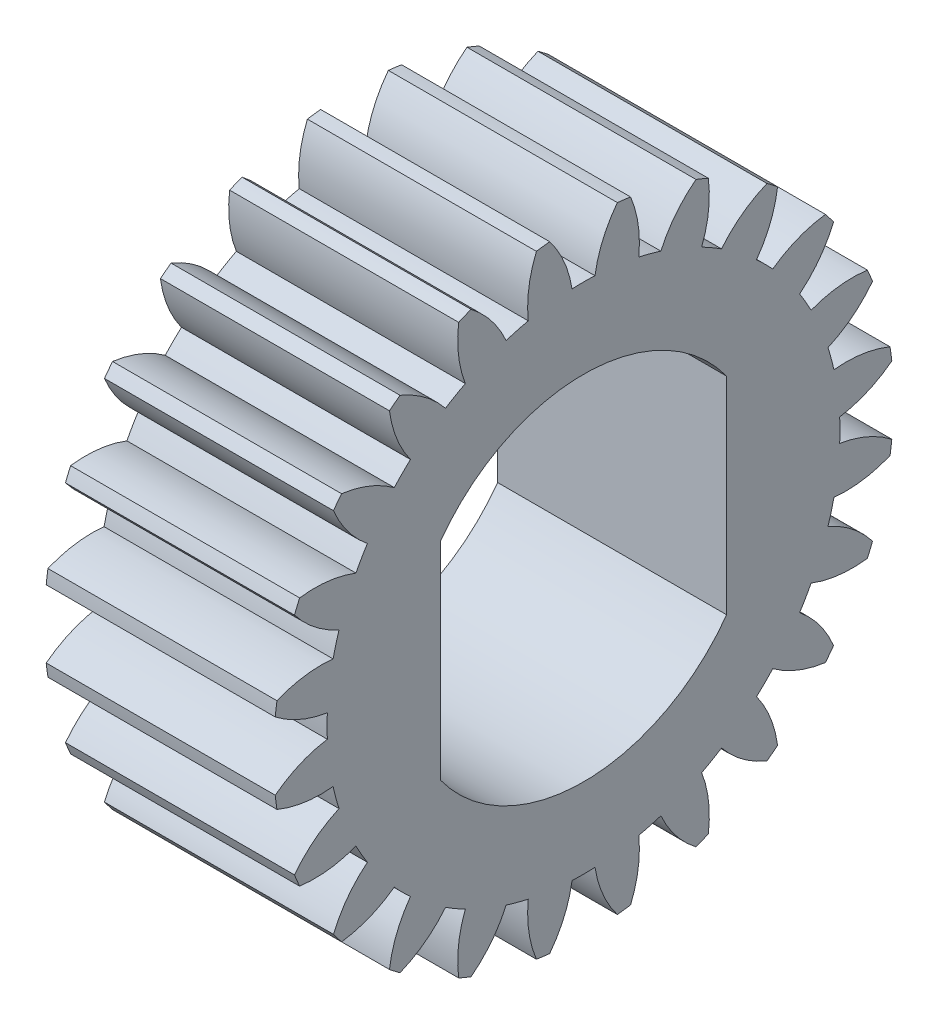
SolidWorks part; units mm, degrees
ref_plane "Plane1" through (0, 0, 0) normal (0, 0, 1) x (1, 0, 0)
ref_plane "Plane2" through (0, 0, 0) normal (0, 1, 0) x (1, 0, 0)
ref_plane "Plane3" through (0, 0, 0) normal (1, 0, 0) x (0, 0, -1)
other "Configuration Table"
sketch "HoldingSke" plane through (0, 0, 0) normal (0, 1, 0) x (1, 0, 0)
  line L0 (0, 0) -> (0.7308, -0.3254)
  line L1 (-15, 0) -> (100, 0) construction
  line L2 (0, 0) -> (-2.1039, 2.3779)
  line L3 (0, 0) -> (-11.863, 4.5341)
  line L4 (0, 0) -> (7.8894, 3.5126)
  line L5 (0, 0) -> (-46.8476, -17.4728)
  line L6 (0, 0) -> (-9.9476, -6.7116)
  line L7 (-2.1039, 2.3779) -> (8.6586, 51.2059)
  line L8 (-76.2, 54.61) -> (-72.9, 54.61)
  line L9 (-71.009, 38.7566) -> (-53.1078, 45.2721)
  line L10 (-76.2, 71.12) -> (104.1128, 71.12)
  line L11 (0, 0) -> (-12, 0)
  line L12 (-76.2, 101.6) -> (-76.155, 101.6)
  line L13 (24.9733, 27.94) -> (52.9518, 28.4284)
  line L14 (24.9733, 27.94) -> (24.9743, 27.94)
  line L15 (24.9733, 27.94) -> (100.4006, 29.5858)
  line L16 (-63.627, -1.25) -> (-12.827, -1.25)
  circle A0 centre (0, 0) radius 12
  circle A1 centre (0, 0) radius 13.4365
  circle A2 centre (0, 0) radius 37.5
  circle A3 centre (0, 0) radius 12
  dimension "MHD" = 26.873
  dimension "Hub_dia" = 75
  dimension "Bore" = 24
  dimension "MBD" = 24
  dimension "Num_teeth" = 24
  dimension "Pitch" = 0.8
  dimension "Overall_len" = 50
  dimension "Show_teeth" = 24
  dimension "Thickness" = 12
  dimension "OAL" = 50.0001
  dimension "T_dim" = 3.3
  dimension "Ap" = 20
  dimension "H" = 19.05
  dimension "Pitch_radius" = 180.3128
  dimension "Width" = 12
  dimension "Backlash" = 0.045
  dimension "Addendum_fac" = 1
  dimension "Dedendum_fac" = 1.25
  dimension "Clearance_fac" = 0.25
  dimension "Dedendum_add" = 0.001
  dimension "Module" = 1.25
sketch "BasProSke" plane through (0, 0, 0) normal (0, 1, 0) x (1, 0, 0)
  line L0 (-10, 0) -> (60, 0) construction
  line L1 (0, 0) -> (0, 16.25)
  line L2 (0, 0) -> (12, 0)
  line L3 (12, 0) -> (12, 16.25)
  line L4 (12, 16.25) -> (0, 16.25)
  dimension "Thickness" = 12
  dimension "Diameter" = 32.5
revolve "Base-Revolve" add sketch "BasProSke" angle 360 about L0
sketch "TooCutSke" plane through (0, 0, 0) normal (1, 0, 0) x (0, 0, -1)
  line L1 (0, 0) -> (0, 107) construction
  line L2 (0, 0) -> (-1.0598, 14.9625) construction
  line L3 (0, 0) -> (-3.9087, 29.6895) construction
  line L4 (-1.0598, 14.9625) -> (-1.9543, 14.8447) construction
  arc A0 (0.6004, 13.4231) -> (-0.6004, 13.4231) centre (0, 0) ccw
  arc A1 (1.7918, 16.1765) -> (-1.7918, 16.1765) centre (0, 0) ccw
  circle A2 centre (0, 0) radius 15 construction
  circle A3 centre (0, 0) radius 14.0954 construction
  arc A4 (-0.6004, 13.4231) -> (-1.7918, 16.1765) centre (-6.5279, 12.4927) ccw
  arc A5 (1.7918, 16.1765) -> (0.6004, 13.4231) centre (6.5279, 12.4927) ccw
  dimension "Root_dia" = 26.873
  dimension "Overcut_dia" = 32.5508
  dimension "Pitch_dia" = 30
  dimension "Base_dia" = 28.1908
  dimension "Flank_rad" = 6
  dimension "Half_ang" = 7.5
  dimension "Half_CT" = 0.9023
extrude "ToothCut" cut sketch "TooCutSke" along normal through all
fillet "Breaks" [suppressed] radius 0.025
fillet "RootFillets" [suppressed] radius 0.3135
pattern_circular "TeethCuts" count 24 every 15 about axis through (-10, 0, 0) along (1, 0, 0) of "ToothCut", "RootFillets", "Breaks"
sketch "HubNeaOneSke" plane through (0, 0, 0) normal (-1, 0, 0) x (0, 0, 1)
  circle A0 centre (0, 0) radius 13.4365
  dimension "Diameter" = 26.873
extrude "HubNearOne" [suppressed] add sketch "HubNeaOneSke" along normal blind 38.0001
sketch "HubNeaBotSke" plane through (0, 0, 0) normal (-1, 0, 0) x (0, 0, 1)
  circle A0 centre (0, 0) radius 13.4365
  dimension "Diameter" = 26.873
extrude "HubNearBoth" [suppressed] add sketch "HubNeaBotSke" along normal blind 19
ref_plane "FarPln" through (12, 0, 0) normal (1, 0, 0) x (0, 0, -1)
sketch "HubFarSke" plane through (12, 0, 0) normal (1, 0, 0) x (0, 0, -1)
  circle A0 centre (0, 0) radius 13.4365
  dimension "Diameter" = 26.873
extrude "HubFar" [suppressed] add sketch "HubFarSke" along normal blind 19
sketch "BorSke" plane through (0, 0, 0) normal (1, 0, 0) x (0, 0, -1)
  circle A0 centre (0, 0) radius 12
  dimension "Diameter" = 24
extrude "Bore" cut sketch "BorSke" along normal mid plane 100.0001
sketch "KeySke" plane through (0, 0, 0) normal (1, 0, 0) x (0, 0, -1)
  line L0 (-4, 0) -> (-4, 15.3)
  line L1 (-4, 15.3) -> (4, 15.3)
  line L2 (4, 15.3) -> (4, 0)
  line L3 (0, 0) -> (0, 34) construction
  line L4 (-4, 0) -> (4, 0)
  dimension "Offset" = 15.3
  dimension "Width" = 8
extrude "Keyway" [suppressed] cut sketch "KeySke" along normal mid plane 100.0001
pattern_circular "Keyway2" [suppressed] count 2 every 90 about axis through (-10, 0, 0) along (1, 0, 0)
sketch "草图1" plane through (0, 0, 0) normal (-1, 0, 0) x (0, 0, 1)
  circle A0 centre (0, 0) radius 9.25
  circle A1 centre (0, 0) radius 12
  dimension "D1" = 18.5
  dimension "D2" = 24
extrude "凸台-拉伸1" add sketch "草图1" against normal through all
sketch "草图2" plane through (0, 0, 0) normal (-1, 0, 0) x (0, 0, 1)
  line L0 (-7.5, 5.4141) -> (-7.5, -5.4141)
  line L8 (0, 9.25) -> (0, 0) construction
  line L9 (7.5, 5.4141) -> (7.5, -5.4141)
  circle A0 centre (0, 0) radius 9.25 construction
  arc A1 (-7.5, 5.4141) -> (-7.5, -5.4141) centre (0, 0) ccw
  arc A2 (7.5, 5.4141) -> (7.5, -5.4141) centre (0, 0) cw
  dimension "D1" = 7.5
extrude "凸台-拉伸2" add sketch "草图2" against normal through all
equation "' \"Module@HoldingSke\" = 6.35"
equation "' \"Num_teeth@HoldingSke\" = 12"
equation "' \"Ap@HoldingSke\" =  20"
equation "' \"Ap@HoldingSke\" = 20"
equation "' \"Width@HoldingSke\" = 0.5 * 25.4"
equation "' \"Hub_dia@HoldingSke\"= 1 * 25.4"
equation "' \"Hub_dia@HoldingSke\" = 1 * 25.4"
equation "' \"Overall_len@HoldingSke\" = 1.0 * 25.4"
equation "' \"Bore@HoldingSke\" = 0.75 * 25.4"
equation "' \"T_dim@HoldingSke\" = 0.1 * 25.4"
equation "' \"Width@KeySke\" = 0.25 * 25.4"
equation "' \"Show_teeth@HoldingSke\" = 13"
equation "' \"Backlash@HoldingSke\" = 0.009 * 25.4"
equation "' \"Addendum_fac@HoldingSke\" = 1.0"
equation "' \"Dedendum_fac@HoldingSke\" = 1.25"
equation "' \"Dedendum_add@HoldingSke\" = 0.00005 * 25.4"
equation "' \"Clearance_fac@HoldingSke\" = 0.25"
equation "\"Pitch@HoldingSke\" = 1 / \"Module@HoldingSke\""
equation "\"Overcut_dia@TooCutSke\" = (\"Num_teeth@HoldingSke\" + 2 * \"Addendum_fac@HoldingSke\") / \"Pitch@HoldingSke\" + 0.002 * 25.4"
equation "\"Pitch_dia@TooCutSke\" = \"Num_teeth@HoldingSke\" / \"Pitch@HoldingSke\""
equation "\"Base_dia@TooCutSke\" = \"Num_teeth@HoldingSke\" / \"Pitch@HoldingSke\" * cos((\"Ap@HoldingSke\"  * 3.14159265 / 180))"
equation "\"Root_dia@TooCutSke\" = (\"Num_teeth@HoldingSke\" + 2) / \"Pitch@HoldingSke\" - 2 * (\"Addendum_fac@HoldingSke\" + \"Dedendum_fac@HoldingSke\") / \"Pitch@HoldingSke\" - \"Dedendum_add@HoldingSke\" * 2"
equation "\"Half_ang@TooCutSke\" = 180 / \"Num_teeth@HoldingSke\""
equation "\"Half_CT@TooCutSke\" = \"Num_teeth@HoldingSke\" / \"Pitch@HoldingSke\" * sin((3.14159265 / 2 / \"Num_teeth@HoldingSke\")) / 2 - 7 * \"Backlash@HoldingSke\" / 4"
equation "\"Flank_rad@TooCutSke\" = \"Num_teeth@HoldingSke\" / \"Pitch@HoldingSke\" / 5"
equation "\"Radius@RootFillets\" = \"Clearance_fac@HoldingSke\" / \"Pitch@HoldingSke\" + \"Dedendum_add@HoldingSke\""
equation "\"Break_rad@Breaks\" = 0.02 / \"Pitch@HoldingSke\""
equation "\"Thickness@HoldingSke\" = \"Width@HoldingSke\""
equation "\"OAL@HoldingSke\" = \"Thickness@HoldingSke\""
equation "\"MHD@HoldingSke\" = (\"Num_teeth@HoldingSke\" + 2) / \"Pitch@HoldingSke\" - 2 * (\"Addendum_fac@HoldingSke\" + \"Dedendum_fac@HoldingSke\")  / \"Pitch@HoldingSke\" - \"Dedendum_add@HoldingSke\" * 2"
equation "\"MBD@HoldingSke\" = (\"Num_teeth@HoldingSke\" + 2) / \"Pitch@HoldingSke\" - 2 * (\"Addendum_fac@HoldingSke\" + \"Dedendum_fac@HoldingSke\")  / \"Pitch@HoldingSke\" - \"Dedendum_add@HoldingSke\" * 2 - 0.002 * 25.4"
equation "\"MHD@HoldingSke\" = ((sgn( \"MHD@HoldingSke\" - \"Hub_dia@HoldingSke\" )-1)*( \"MHD@HoldingSke\" - \"Hub_dia@HoldingSke\" ))/-2+ \"Hub_dia@HoldingSke\""
equation "\"MBD@HoldingSke\" = ((sgn( \"MBD@HoldingSke\" - \"Bore@HoldingSke\" )-1)*( \"MBD@HoldingSke\" - \"Bore@HoldingSke\" ))/-2+ \"Bore@HoldingSke\""
equation "\"OAL@HoldingSke\" = ((sgn( \"OAL@HoldingSke\" - \"Overall_len@HoldingSke\" )+1)*( \"OAL@HoldingSke\" - \"Overall_len@HoldingSke\" ))/2 + \"Overall_len@HoldingSke\" + 0.000002 * 25.4"
equation "\"Num_teeth@TeethCuts\" = int( \"Show_teeth@HoldingSke\" ) + 1"
equation "\"Num_teeth@TeethCuts\" = ((sgn( \"Num_teeth@TeethCuts\" - \"Num_teeth@HoldingSke\" )-1)*( \"Num_teeth@TeethCuts\" - \"Num_teeth@HoldingSke\" ))/-2+ \"Num_teeth@HoldingSke\""
equation "\"Num_teeth@TeethCuts\" = ((sgn( \"Num_teeth@TeethCuts\" - 2.0)+1)*( \"Num_teeth@TeethCuts\" - 2.0))/2 +2.0"
equation "\"Angle@TeethCuts\" = 360.0 / \"Num_teeth@HoldingSke\""
equation "\"Diameter@BasProSke\" = (\"Num_teeth@HoldingSke\" + 2 * \"Addendum_fac@HoldingSke\") / \"Pitch@HoldingSke\""
equation "\"Thickness@BasProSke\"  = \"Thickness@HoldingSke\""
equation "' \"Fillet_rad@BasProSke\" =  \"Thickness@HoldingSke\" * 0.05"
equation "' \"Fillet_rad@BasProSke\" = \"Thickness@HoldingSke\" * 0.05"
equation "\"MHD@HoldingSke\" = ((sgn( \"MHD@HoldingSke\" - \"Root_dia@TooCutSke\" )-1)*( \"MHD@HoldingSke\" - \"Root_dia@TooCutSke\" ))/-2+ \"Root_dia@TooCutSke\""
equation "\"Diameter@HubNeaOneSke\" = \"MHD@HoldingSke\""
equation "\"Length@HubNearOne\" = \"OAL@HoldingSke\" - \"Thickness@BasProSke\""
equation "\"Diameter@HubNeaBotSke\" = \"MHD@HoldingSke\""
equation "\"Length@HubNearBoth\" = ( \"OAL@HoldingSke\" - \"Thickness@BasProSke\" ) / 2.0"
equation "\"Thickness@FarPln\" = \"Thickness@BasProSke\""
equation "\"Diameter@HubFarSke\" = \"MHD@HoldingSke\""
equation "\"Length@HubFar\" = ( \"OAL@HoldingSke\" - \"Thickness@BasProSke\" ) / 2.0"
equation "\"Diameter@BorSke\" = \"MBD@HoldingSke\""
equation "\"D1@Bore\" = \"OAL@HoldingSke\" * 2.0"
equation "\"D1@Keyway\" = \"OAL@HoldingSke\" * 2.0"
equation "\"Offset@KeySke\" = \"T_dim@HoldingSke\" + \"MBD@HoldingSke\" / 2.0"
